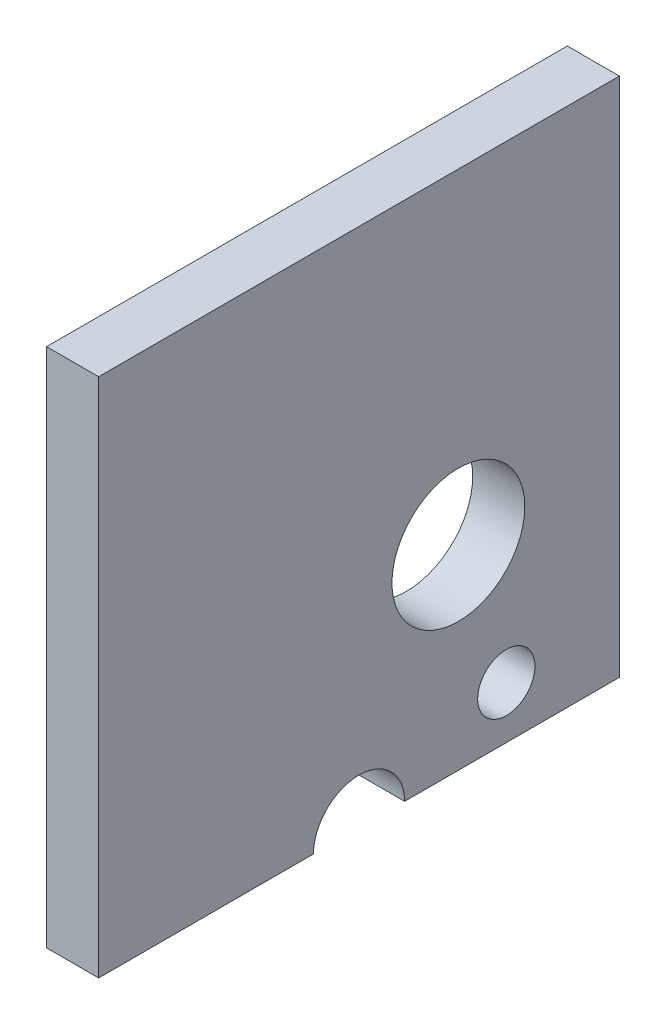
SolidWorks part; units mm, degrees
ref_plane "前视基准面" through (0, 0, 0) normal (0, 0, 1) x (1, 0, 0)
ref_plane "上视基准面" through (0, 0, 0) normal (0, 1, 0) x (1, 0, 0)
ref_plane "右视基准面" through (0, 0, 0) normal (1, 0, 0) x (0, 0, -1)
other "Configuration Table"
sketch "草图1" plane through (0, 0, 0) normal (1, 0, 0) x (0, 0, -1)
  line L1 (0, 0) -> (20, 0)
  line L2 (0, 0) -> (0, -20)
  line L3 (0, -20) -> (20, -20)
  line L4 (20, 0) -> (20, -20)
  circle A0 centre (10, -20) radius 1.75
  dimension "D1" = 20
  dimension "D3" = 3.5
  dimension "D2" = 20
extrude "凸台-拉伸1" add sketch "草图1" along normal blind 2 contours A0 L3 L4 L1 L2
sketch "草图2" plane through (2, 0, 0) normal (1, 0, 0) x (0, 0, -1)
  circle A0 centre (15.6569, -18) radius 1.1
  arc A1 (11.75, -20) -> (8.25, -20) centre (10, -20) ccw construction
  circle A2 centre (13.8157, -12.5) radius 2.55
  point P2 (10, -20)
  dimension "D1" = 2.2
  dimension "D5" = 5.1
  dimension "D2" = 6
  dimension "D3" = 2
  dimension "D4" = 5.8
  dimension "D8" = 7.5
extrude "切除-拉伸1" cut sketch "草图2" against normal through all
